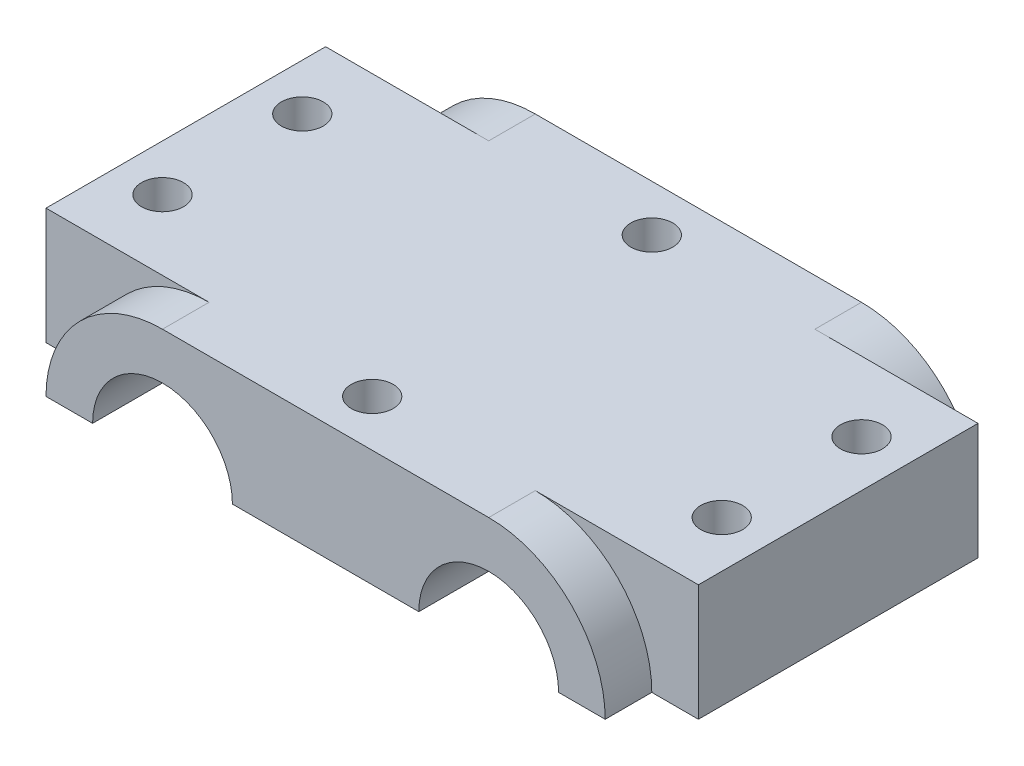
SolidWorks part; units mm, degrees
ref_plane "Front Plane" through (0, 0, 0) normal (0, 0, 1) x (1, 0, 0)
ref_plane "Top Plane" through (0, 0, 0) normal (0, 1, 0) x (1, 0, 0)
ref_plane "Right Plane" through (0, 0, 0) normal (1, 0, 0) x (0, 0, -1)
sketch "Sketch1" plane through (0, 0, 0) normal (0, 0, 1) x (1, 0, 0)
  line L0 (0, 0) -> (0, -23414.8813) construction
  line L1 (0, 0) -> (-23414.8813, 0) construction
  line L2 (-10, 0) -> (10, 0)
  line L3 (-17.5, 12.5) -> (17.5, 12.5)
  line L4 (-30, 0) -> (-25, 0)
  line L5 (30, 0) -> (25, 0)
  arc A0 (-10, 0) -> (-25, 0) centre (-17.5, 0) ccw
  arc A1 (-17.5, 12.5) -> (-30, 0) centre (-17.5, 0) ccw
  arc A2 (17.5, 12.5) -> (30, 0) centre (17.5, 0) cw
  arc A3 (10, 0) -> (25, 0) centre (17.5, 0) cw
  point P12 (0, 0)
  point P17 (0, 12.5)
  dimension "D1" = 17.5
  dimension "D2" = 7.5
  dimension "D3" = 12.5
extrude "Boss-Extrude1" add sketch "Sketch1" along normal mid plane 40
sketch "Sketch2" plane through (0, 0, 0) normal (0, 0, 1) x (1, 0, 0)
  line L0 (-35, 0) -> (-35, 12.5)
  line L2 (-35, 0) -> (-30, 0)
  line L3 (-17.5, 12.5) -> (-35, 12.5)
  line L4 (0, 0) -> (0, -50000) construction
  line L5 (-10, 0) -> (10, 0) construction
  line L6 (35, 0) -> (30, 0)
  line L7 (35, 0) -> (35, 12.5)
  line L8 (17.5, 12.5) -> (35, 12.5)
  arc A0 (-17.5, 12.5) -> (-30, 0) centre (-17.5, 0) ccw construction
  arc A1 (-17.5, 12.5) -> (-30, 0) centre (-17.5, 0) ccw
  arc A2 (30, 0) -> (17.5, 12.5) centre (17.5, 0) ccw construction
  arc A3 (30, 0) -> (17.5, 12.5) centre (17.5, 0) ccw
  arc A4 (17.5, 12.5) -> (30, 0) centre (17.5, 0) cw
  point P12 (0, 0)
  dimension "D1" = 17.5
extrude "Boss-Extrude2" add sketch "Sketch2" along normal mid plane 30 contours A1 L3 L0 L2 | A3 L6 L7 L8
hole_wizard "Ø3.0mm Dowel Hole1" positions "Sketch3" profile "Sketch4" hole size "Ø3.0" standard "ISO" end condition through all
sketch "Sketch3" plane through (0, 12.5, 0) normal (0, 1, 0) x (1, 0, 0)
  line L0 (17.5, 20) -> (-17.5, 20) construction
  line L1 (-30, 15) -> (-30, 20) construction
  line L2 (30, 15) -> (17.5, 15) construction
  line L3 (30, 15) -> (30, 20) construction
  point P0 (0, 15)
  point P2 (0, -15)
  point P4 (30, 7.5)
  point P6 (30, -7.5)
  point P8 (-30, -7.5)
  point P10 (-30, 7.5)
  dimension "D1" = 5
  dimension "D2" = 30
  dimension "D3" = 30
  dimension "D4" = 15
  dimension "D5" = 7.5
  dimension "D6" = 0
  dimension "D7" = 0
sketch "Sketch4" plane through (0, 12.5, -15) normal (1, 0, 0) x (0, 0, 1)
  line L0 (0, 0) -> (0, 12.5)
  line L1 (0, 12.5) -> (2.25, 12.5)
  line L2 (2.25, 12.5) -> (2.25, 0)
  line L5 (2.25, 0) -> (0, 0)
  line L11 (0, -6.35) -> (0, 107.95) construction
  dimension "Thru Hole Dia." = 4.5
  dimension "Thru Hole Depth" = 12.5
